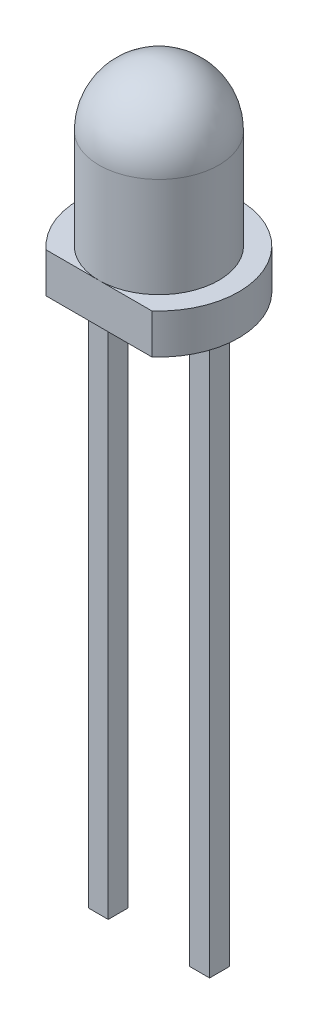
SolidWorks part; units mm, degrees
ref_plane "Front Plane" through (0, 0, 0) normal (0, 0, 1) x (1, 0, 0)
ref_plane "Top Plane" through (0, 0, 0) normal (0, 1, 0) x (1, 0, 0)
ref_plane "Right Plane" through (0, 0, 0) normal (1, 0, 0) x (0, 0, -1)
sketch "Sketch1" plane through (0, 0, 0) normal (1, 0, 0) x (0, 0, -1)
  line L0 (-1.5, 0) -> (-1.5, 3.5)
  line L1 (0, 5) -> (0, 0) construction
  line L2 (0, 0) -> (-1.5, 0)
  line L3 (0, 5) -> (0, 0)
  arc A0 (-1.5, 3.5) -> (0, 5) centre (0, 3.5) cw
  dimension "D1" = 3
  dimension "D2" = 5
revolve "Revolve1" add sketch "Sketch1" angle 360 about L1
sketch "Sketch2" plane through (0, 0, 0) normal (0, 1, 0) x (1, 0, 0)
  line L0 (-1.3229, -1.5) -> (1.3229, -1.5)
  arc A0 (1.3229, -1.5) -> (-1.3229, -1.5) centre (0, 0) ccw
  circle A1 centre (0, 0) radius 1.5 construction
  dimension "D1" = 4
extrude "Boss-Extrude1" add sketch "Sketch2" along normal blind 1
sketch "Sketch3" plane through (0, 0, 0) normal (0, -1, 0) x (1, 0, 0)
  line L1 (-1.52, 0.25) -> (-1.02, 0.25)
  line L2 (-1.52, 0.25) -> (-1.52, -0.25)
  line L3 (-1.52, -0.25) -> (-1.02, -0.25)
  line L4 (-1.02, 0.25) -> (-1.02, -0.25)
  line L5 (1.02, 0.25) -> (1.52, 0.25)
  line L6 (1.02, 0.25) -> (1.02, -0.25)
  line L7 (1.02, -0.25) -> (1.52, -0.25)
  line L8 (1.52, 0.25) -> (1.52, -0.25)
  point P8 (-1.02, 0)
  point P9 (1.02, 0)
  point P11 (-1.27, 0.25)
  point P12 (1.27, 0.25)
  dimension "D1" = 0.5
  dimension "D2" = 2.54
  dimension "D3" = 1.27
extrude "Boss-Extrude2" add sketch "Sketch3" along normal blind 14 separate body
